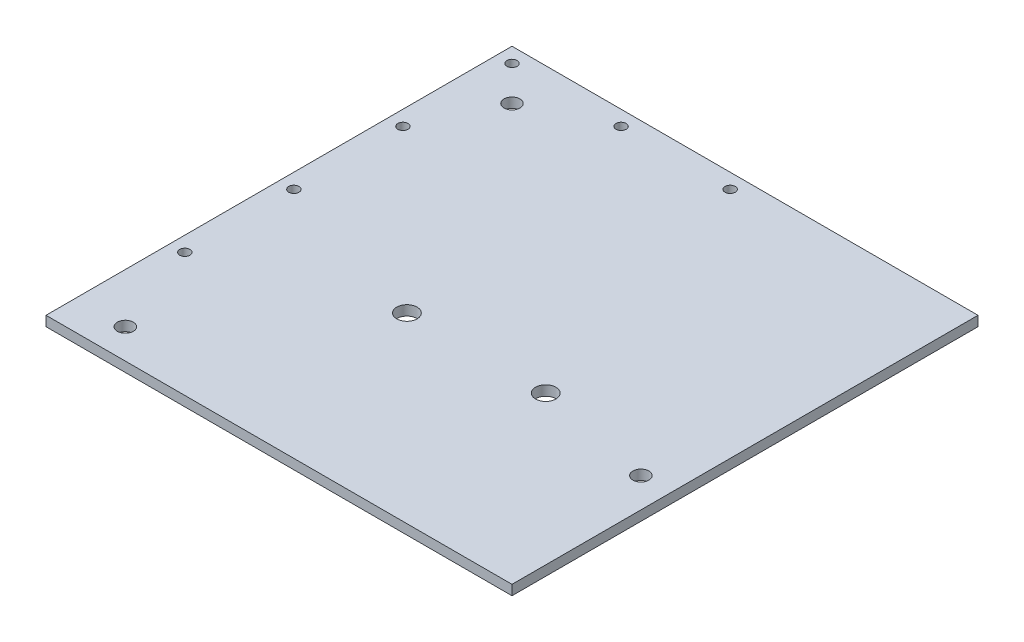
SolidWorks part; units mm, degrees
material "6061 Alloy"
ref_plane "Front Plane" through (0, 0, 0) normal (0, 0, 1) x (1, 0, 0)
ref_plane "Top Plane" through (0, 0, 0) normal (0, 1, 0) x (1, 0, 0)
ref_plane "Right Plane" through (0, 0, 0) normal (1, 0, 0) x (0, 0, -1)
sketch "Sketch1" plane through (0, 0, 0) normal (0, 1, 0) x (1, 0, 0)
  line L0 (-69.85, -69.85) -> (-79.375, -69.85)
  line L1 (-69.85, -69.85) -> (69.85, -69.85)
  line L2 (-69.85, -69.85) -> (-69.85, 69.85) construction
  line L3 (-69.85, 69.85) -> (69.85, 69.85) construction
  line L4 (69.85, -69.85) -> (69.85, 69.85)
  line L5 (-69.85, -69.85) -> (69.85, 69.85) construction
  line L6 (-69.85, 69.85) -> (69.85, -69.85) construction
  line L7 (-79.375, -69.85) -> (-79.375, 79.375)
  line L8 (-79.375, 79.375) -> (69.85, 79.375)
  line L9 (69.85, 79.375) -> (69.85, 69.85)
  point P0 (0, 0)
  dimension "D1" = 139.7
  dimension "D2" = 139.7
  dimension "D3" = 9.525
  dimension "D4" = 9.525
extrude "Boss-Extrude1" add sketch "Sketch1" along normal mid plane 3.175
hole_wizard "#4 Clearance Hole1" positions "Sketch3" profile "Sketch2" hole size "#4" standard "ANSI Inch" end condition through all
sketch "Sketch3" plane through (0, 1.5875, 0) normal (0, 1, 0) x (1, 0, 0)
  line L0 (-74.6125, -69.85) -> (-74.6125, 79.375) construction
  line L1 (-79.375, -69.85) -> (69.85, -69.85) construction
  line L2 (69.85, 79.375) -> (-79.375, 79.375) construction
  line L4 (-79.375, 79.375) -> (-79.375, -69.85) construction
  line L5 (-79.375, 74.6125) -> (69.85, 74.6125) construction
  point P13 (-74.6125, 4.7625)
  point P15 (-74.6125, 39.6875)
  point P17 (-74.6125, 74.6125)
  point P19 (-39.6875, 74.6125)
  point P21 (-4.7625, 74.6125)
  point P27 (-74.6125, -30.1625)
  dimension "D1" = 4.7625
  dimension "D2" = 4.7625
  dimension "D3" = 34.925
  dimension "D4" = 34.925
  dimension "D5" = 34.925
  dimension "D6" = 34.925
  dimension "D7" = 34.925
sketch "Sketch2" plane through (-74.6125, 1.5875, -4.7625) normal (1, 0, 0) x (0, 0, 1)
  line L0 (0, 0) -> (0, 3.175)
  line L1 (0, 3.175) -> (1.6319, 3.175)
  line L2 (1.6319, 3.175) -> (1.6319, 0)
  line L5 (1.6319, 0) -> (0, 0)
  line L11 (0, -6.35) -> (0, 107.95) construction
  dimension "Thru Hole Dia." = 3.2639
  dimension "Thru Hole Depth" = 3.175
hole_wizard "#10 Clearance Hole1" positions "Sketch5" profile "Sketch4" hole size "#10" standard "ANSI Inch" end condition up to next
sketch "Sketch5" plane through (0, 1.5875, 0) normal (0, 1, 0) x (1, 0, 0)
  line L0 (-79.375, 79.375) -> (-79.375, -69.85) construction
  line L1 (-79.375, -69.85) -> (69.85, -69.85) construction
  line L2 (69.85, -69.85) -> (69.85, 79.375) construction
  line L3 (69.85, 79.375) -> (-79.375, 79.375) construction
  point P0 (-63.5, -60.325)
  point P2 (-63.5, 63.5)
  point P4 (60.325, -19.05)
  point P17 (-22.225, -11.43)
  point P19 (22.225, -11.43)
  dimension "D1" = 15.875
  dimension "D2" = 9.525
  dimension "D3" = 50.8
  dimension "D4" = 9.525
  dimension "D5" = 15.875
  dimension "D6" = 47.625
  dimension "D7" = 92.075
  dimension "D8" = 58.42
sketch "Sketch4" plane through (-63.5, 1.5875, 60.325) normal (1, 0, 0) x (0, 0, 1)
  line L0 (0, 0) -> (0, 3.175)
  line L1 (0, 3.175) -> (2.5527, 3.175)
  line L2 (2.5527, 3.175) -> (2.5527, 0)
  line L5 (2.5527, 0) -> (0, 0)
  line L11 (0, -6.35) -> (0, 107.95) construction
  dimension "Thru Hole Dia." = 5.1054
  dimension "Thru Hole Depth" = 3.175
hole_wizard "1/4 Clearance Hole1" positions "Sketch7" profile "Sketch6" hole size "1/4" standard "ANSI Inch" end condition through all
sketch "Sketch7" plane through (0, 1.5875, 0) normal (0, 1, 0) x (1, 0, 0)
  point P0 (-22.225, -11.43)
  point P3 (22.225, -11.43)
sketch "Sketch6" plane through (-22.225, 1.5875, 11.43) normal (1, 0, 0) x (0, 0, 1)
  line L0 (0, 0) -> (0, 3.175)
  line L1 (0, 3.175) -> (3.2639, 3.175)
  line L2 (3.2639, 3.175) -> (3.2639, 0)
  line L5 (3.2639, 0) -> (0, 0)
  line L11 (0, -6.35) -> (0, 107.95) construction
  dimension "Thru Hole Dia." = 6.5278
  dimension "Thru Hole Depth" = 3.175
